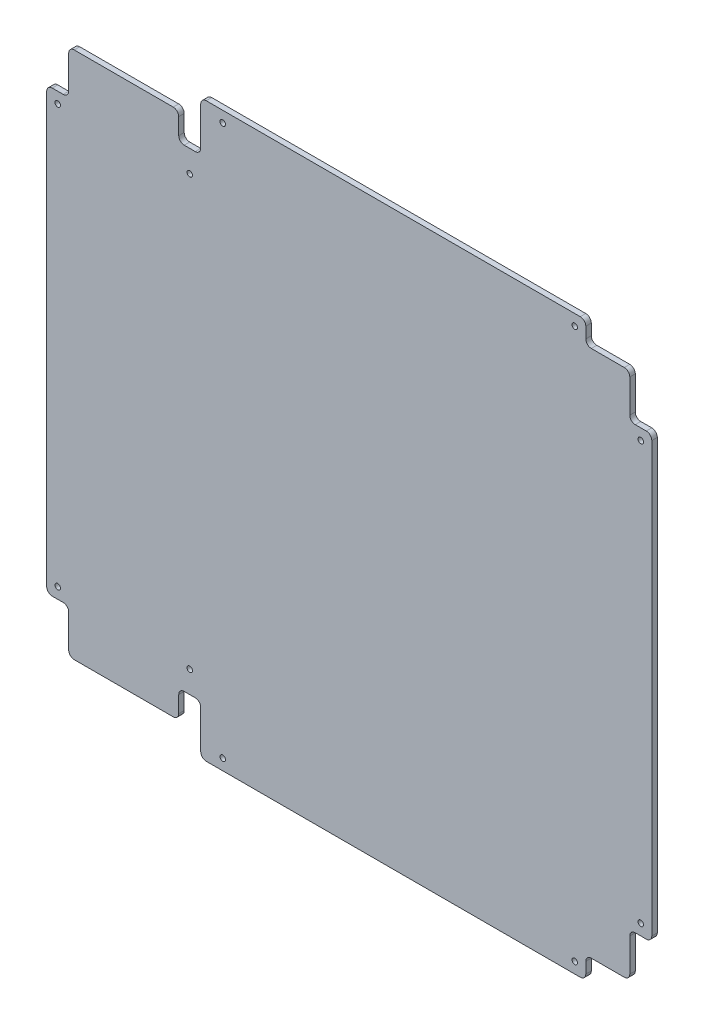
SolidWorks part; units mm, degrees
material "丙烯酸(中高冲击)"
ref_plane "前视基准面" through (0, 0, 0) normal (0, 0, 1) x (1, 0, 0)
ref_plane "上视基准面" through (0, 0, 0) normal (0, 1, 0) x (1, 0, 0)
ref_plane "右视基准面" through (0, 0, 0) normal (1, 0, 0) x (0, 0, -1)
sketch "草图1" plane through (0, 0, 0) normal (0, 0, 1) x (1, 0, 0)
  line L1 (-275, 260) -> (275, 260)
  line L2 (-275, 260) -> (-275, -260)
  line L3 (-275, -260) -> (275, -260)
  line L4 (275, 260) -> (275, -260)
  line L5 (-275, 260) -> (275, -260) construction
  line L6 (-275, -260) -> (275, 260) construction
  point P0 (0, 0)
  dimension "D1" = 520
  dimension "D2" = 550
extrude "凸台-拉伸1" add sketch "草图1" along normal blind 5
sketch "草图2" plane through (0, 0, 5) normal (0, 0, 1) x (1, 0, 0)
  line L0 (255, 240) -> (215, 240)
  line L2 (-255, -240) -> (-155, -240)
  line L3 (255, -240) -> (255, -200)
  line L4 (275, -260) -> (275, 260)
  line L5 (275, 260) -> (-275, 260)
  line L6 (-275, 260) -> (-275, -260)
  line L7 (-275, -260) -> (275, -260)
  line L8 (275, -260) -> (275, -200)
  line L9 (275, 260) -> (215, 260)
  line L11 (-275, -260) -> (-135, -260)
  line L13 (215, 260) -> (215, 240)
  line L14 (255, 200) -> (275, 200)
  line L15 (255, -200) -> (275, -200)
  line L17 (215, -240) -> (215, -260)
  line L18 (-255, -200) -> (-275, -200)
  line L20 (-275, -200) -> (-275, -260)
  line L21 (-275, 260) -> (-275, -260) construction
  line L22 (-255, -200) -> (-255, -240)
  line L23 (-255, 240) -> (-255, -240) construction
  line L24 (255, 200) -> (255, 240)
  line L25 (255, -240) -> (255, 240) construction
  line L26 (275, 200) -> (275, 260)
  line L27 (275, -260) -> (275, 260) construction
  line L28 (215, -260) -> (275, -260)
  line L29 (-275, -260) -> (275, -260) construction
  line L30 (215, -240) -> (255, -240)
  line L31 (-255, -240) -> (255, -240) construction
  line L33 (255, 240) -> (-255, 240) construction
  line L35 (275, 260) -> (-275, 260) construction
  line L36 (-135, -260) -> (-135, -215)
  line L37 (-135, -215) -> (-155, -215)
  line L38 (-155, -215) -> (-155, -240)
  line L39 (-275, 260) -> (-275, -260) construction
  line L40 (55, 0) -> (-55, 0) construction
  line L41 (-275, 260) -> (-135, 260)
  line L42 (-275, 200) -> (-275, 260)
  line L43 (-255, 200) -> (-275, 200)
  line L44 (-255, 200) -> (-255, 240)
  line L45 (-255, 240) -> (-155, 240)
  line L46 (-155, 215) -> (-155, 240)
  line L47 (-135, 215) -> (-155, 215)
  line L48 (-135, 260) -> (-135, 215)
  line L49 (275, 260) -> (-275, 260) construction
  line L50 (-275, -260) -> (275, -260) construction
  circle A1 centre (205, 250) radius 2.5
  circle A2 centre (265, 190) radius 2.5
  circle A4 centre (-265, -190) radius 2.5
  circle A6 centre (205, -250) radius 2.5
  circle A7 centre (265, -190) radius 2.5
  circle A8 centre (-265, 190) radius 2.5
  circle A9 centre (-115, 250) radius 2.5
  circle A10 centre (-115, -250) radius 2.5
  circle A11 centre (-145, -195) radius 2.5
  circle A12 centre (-145, 195) radius 2.5
  dimension "D10" = 20
  dimension "D11" = 140
  dimension "D12" = 10
  dimension "D13" = 5
  dimension "D14" = 10
  dimension "D16" = 5
  dimension "D17" = 10
  dimension "D19" = 5
  dimension "D20" = 10
  dimension "D21" = 10
  dimension "D22" = 5
  dimension "D24" = 10
  dimension "D25" = 40
  dimension "D26" = 20
  dimension "D27" = 10
  dimension "D28" = 5
  dimension "D29" = 10
  dimension "D30" = 5
  dimension "D31" = 10
  dimension "D3" = 5
  dimension "D33" = 5
  dimension "D34" = 10
  dimension "D36" = 5
  dimension "D37" = 20
  dimension "D38" = 10
  dimension "D4" = 60
  dimension "D5" = 60
  dimension "D6" = 60
  dimension "D7" = 60
  dimension "D8" = 45
  dimension "D9" = 60
  dimension "D15" = 10
  dimension "D18" = 10
  dimension "D23" = 10
  dimension "D32" = 20
  dimension "D35" = 20
  dimension "D1" = 0
  dimension "D2" = 20
extrude "切除-拉伸1" cut sketch "草图2" against normal through all
fillet "圆角1" radius 5 24 edges at (-255, -240, 2.5) (-255, -200, 2.5) (-275, -200, 2.5) (215, -260, 2.5) (215, -240, 2.5) (255, -240, 2.5) (255, -200, 2.5) (275, -200, 2.5) (275, 200, 2.5) (255, 200, 2.5) (255, 240, 2.5) (215, 260, 2.5) (215, 240, 2.5) (-135, -215, 2.5) (-135, -260, 2.5) (-155, -240, 2.5) (-155, -215, 2.5) (-275, 200, 2.5) (-255, 200, 2.5) (-255, 240, 2.5) (-155, 240, 2.5) (-155, 215, 2.5) (-135, 215, 2.5) (-135, 260, 2.5)
